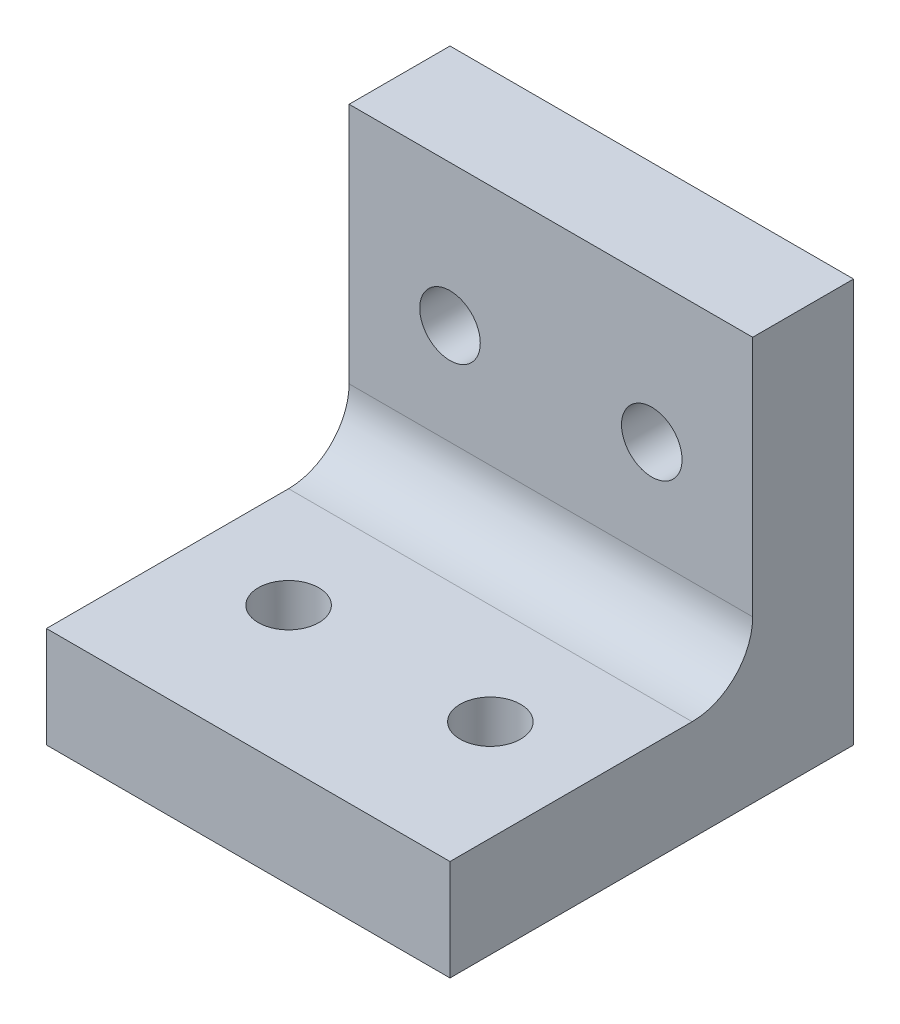
SolidWorks part; units mm, degrees
ref_plane "Front Plane" through (0, 0, 0) normal (0, 0, 1) x (1, 0, 0)
ref_plane "Top Plane" through (0, 0, 0) normal (0, 1, 0) x (1, 0, 0)
ref_plane "Right Plane" through (0, 0, 0) normal (1, 0, 0) x (0, 0, -1)
sketch "Sketch1" plane through (0, 0, 0) normal (0, 1, 0) x (1, 0, 0)
  line L1 (-10, -10) -> (10, -10)
  line L2 (-10, -10) -> (-10, 10)
  line L3 (-10, 10) -> (10, 10)
  line L4 (10, -10) -> (10, 10)
  line L5 (-10, -10) -> (10, 10) construction
  line L6 (-10, 10) -> (10, -10) construction
  point P0 (0, 0)
extrude "Boss-Extrude1" add sketch "Sketch1" along normal blind 5
sketch "Sketch2" plane through (0, 5, 0) normal (0, 1, 0) x (1, 0, 0)
  line L2 (-10, 10) -> (-10, 5)
  line L4 (10, 10) -> (10, 5)
  line L5 (-10, 10) -> (10, 10)
  line L6 (-10, 5) -> (10, 5)
  line L8 (10, 10) -> (-10, 10) construction
  point P0 (0, 10)
extrude "Boss-Extrude2" add sketch "Sketch2" along normal blind 15
sketch "Sketch3" plane through (0, 5, 0) normal (0, 1, 0) x (1, 0, 0)
  line L0 (0, -10) -> (0, -3) construction
  line L1 (-10, -10) -> (10, -10) construction
  line L3 (-6.5, -3) -> (6.5, -3) construction
  circle A0 centre (-5, -3) radius 1.5
  circle A1 centre (5, -3) radius 1.5
  dimension "D1" = 7
extrude "Cut-Extrude1" cut sketch "Sketch3" against normal through all both and the other way through all
sketch "Sketch4" plane through (0, 0, -5) normal (0, 0, 1) x (1, 0, 0)
  line L0 (0, 20) -> (0, 13) construction
  line L1 (-10, 20) -> (10, 20) construction
  line L3 (-6.5, 13) -> (6.5, 13) construction
  circle A0 centre (-5, 13) radius 1.5
  circle A1 centre (5, 13) radius 1.5
extrude "Cut-Extrude2" cut sketch "Sketch4" against normal through all both
fillet "Fillet1" radius 3 1 edges at (0, 5, -5)
